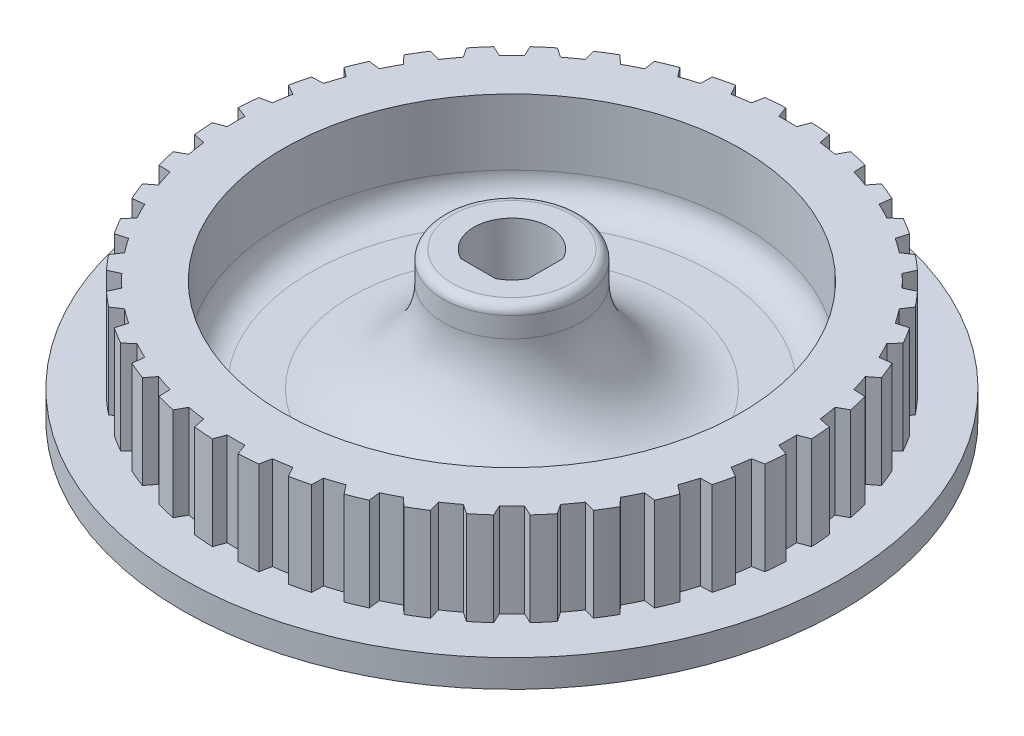
SolidWorks part; units mm, degrees
ref_plane "Спереди" through (0, 0, 0) normal (0, 0, 1) x (1, 0, 0)
ref_plane "Сверху" through (0, 0, 0) normal (0, 1, 0) x (1, 0, 0)
ref_plane "Справа" through (0, 0, 0) normal (1, 0, 0) x (0, 0, -1)
sketch "Эскиз1" plane through (0, 0, 0) normal (0, 1, 0) x (1, 0, 0)
  line L0 (0, 32.35) -> (0, 0) construction
  line L1 (0.975, 30.1342) -> (1.406, 31.3185)
  line L2 (-0.975, 30.1342) -> (-1.406, 31.3185)
  line L3 (3.751, 29.9158) -> (3.5106, 31.1528)
  line L4 (5.677, 29.6107) -> (6.288, 30.7129)
  line L5 (8.3847, 28.9606) -> (8.3407, 30.2201)
  line L6 (10.2393, 28.3581) -> (11.0151, 29.3511)
  line L7 (12.8119, 27.2924) -> (12.9655, 28.5433)
  line L8 (14.5494, 26.4072) -> (15.4711, 27.2666)
  line L9 (16.9237, 24.9522) -> (17.271, 26.1636)
  line L10 (18.5012, 23.806) -> (19.546, 24.5107)
  line L11 (20.6187, 21.9975) -> (21.1513, 23.1397)
  line L12 (21.9975, 20.6187) -> (23.1397, 21.1513)
  line L13 (23.806, 18.5012) -> (24.5107, 19.546)
  line L14 (24.9522, 16.9237) -> (26.1636, 17.271)
  line L15 (26.4072, 14.5494) -> (27.2666, 15.4711)
  line L16 (27.2924, 12.8119) -> (28.5433, 12.9655)
  line L17 (28.3581, 10.2393) -> (29.3511, 11.0151)
  line L18 (28.9606, 8.3847) -> (30.2201, 8.3407)
  line L19 (29.6107, 5.677) -> (30.7129, 6.288)
  line L20 (29.9158, 3.751) -> (31.1528, 3.5106)
  line L21 (30.1342, 0.975) -> (31.3185, 1.406)
  line L22 (30.1342, -0.975) -> (31.3185, -1.406)
  line L23 (29.9158, -3.751) -> (31.1528, -3.5106)
  line L24 (29.6107, -5.677) -> (30.7129, -6.288)
  line L25 (28.9606, -8.3847) -> (30.2201, -8.3407)
  line L26 (28.3581, -10.2393) -> (29.3511, -11.0151)
  line L27 (27.2924, -12.8119) -> (28.5433, -12.9655)
  line L28 (26.4072, -14.5494) -> (27.2666, -15.4711)
  line L29 (24.9522, -16.9237) -> (26.1636, -17.271)
  line L30 (23.806, -18.5012) -> (24.5107, -19.546)
  line L31 (21.9975, -20.6187) -> (23.1397, -21.1513)
  line L32 (20.6187, -21.9975) -> (21.1513, -23.1397)
  line L33 (18.5012, -23.806) -> (19.546, -24.5107)
  line L34 (16.9237, -24.9522) -> (17.271, -26.1636)
  line L35 (14.5494, -26.4072) -> (15.4711, -27.2666)
  line L36 (12.8119, -27.2924) -> (12.9655, -28.5433)
  line L37 (10.2393, -28.3581) -> (11.0151, -29.3511)
  line L38 (8.3847, -28.9606) -> (8.3407, -30.2201)
  line L39 (5.677, -29.6107) -> (6.288, -30.7129)
  line L40 (3.751, -29.9158) -> (3.5106, -31.1528)
  line L41 (0.975, -30.1342) -> (1.406, -31.3185)
  line L42 (-0.975, -30.1342) -> (-1.406, -31.3185)
  line L43 (-3.751, -29.9158) -> (-3.5106, -31.1528)
  line L44 (-5.677, -29.6107) -> (-6.288, -30.7129)
  line L45 (-8.3847, -28.9606) -> (-8.3407, -30.2201)
  line L46 (-10.2393, -28.3581) -> (-11.0151, -29.3511)
  line L47 (-12.8119, -27.2924) -> (-12.9655, -28.5433)
  line L48 (-14.5494, -26.4072) -> (-15.4711, -27.2666)
  line L49 (-16.9237, -24.9522) -> (-17.271, -26.1636)
  line L50 (-18.5012, -23.806) -> (-19.546, -24.5107)
  line L51 (-20.6187, -21.9975) -> (-21.1513, -23.1397)
  line L52 (-21.9975, -20.6187) -> (-23.1397, -21.1513)
  line L53 (-23.806, -18.5012) -> (-24.5107, -19.546)
  line L54 (-24.9522, -16.9237) -> (-26.1636, -17.271)
  line L55 (-26.4072, -14.5494) -> (-27.2666, -15.4711)
  line L56 (-27.2924, -12.8119) -> (-28.5433, -12.9655)
  line L57 (-28.3581, -10.2393) -> (-29.3511, -11.0151)
  line L58 (-28.9606, -8.3847) -> (-30.2201, -8.3407)
  line L59 (-29.6107, -5.677) -> (-30.7129, -6.288)
  line L60 (-29.9158, -3.751) -> (-31.1528, -3.5106)
  line L61 (-30.1342, -0.975) -> (-31.3185, -1.406)
  line L62 (-30.1342, 0.975) -> (-31.3185, 1.406)
  line L63 (-29.9158, 3.751) -> (-31.1528, 3.5106)
  line L64 (-29.6107, 5.677) -> (-30.7129, 6.288)
  line L65 (-28.9606, 8.3847) -> (-30.2201, 8.3407)
  line L66 (-28.3581, 10.2393) -> (-29.3511, 11.0151)
  line L67 (-27.2924, 12.8119) -> (-28.5433, 12.9655)
  line L68 (-26.4072, 14.5494) -> (-27.2666, 15.4711)
  line L69 (-24.9522, 16.9237) -> (-26.1636, 17.271)
  line L70 (-23.806, 18.5012) -> (-24.5107, 19.546)
  line L71 (-21.9975, 20.6187) -> (-23.1397, 21.1513)
  line L72 (-20.6187, 21.9975) -> (-21.1513, 23.1397)
  line L73 (-18.5012, 23.806) -> (-19.546, 24.5107)
  line L74 (-16.9237, 24.9522) -> (-17.271, 26.1636)
  line L75 (-14.5494, 26.4072) -> (-15.4711, 27.2666)
  line L76 (-12.8119, 27.2924) -> (-12.9655, 28.5433)
  line L77 (-10.2393, 28.3581) -> (-11.0151, 29.3511)
  line L78 (-8.3847, 28.9606) -> (-8.3407, 30.2201)
  line L79 (-5.677, 29.6107) -> (-6.288, 30.7129)
  line L80 (-3.751, 29.9158) -> (-3.5106, 31.1528)
  circle A0 centre (0, 0) radius 30.15 construction
  circle A1 centre (0, 0) radius 32.35 construction
  circle A2 centre (0, 0) radius 31.85 construction
  circle A3 centre (0, 0) radius 31.35 construction
  arc A4 (-0.975, 30.1342) -> (0.975, 30.1342) centre (0, 0) cw
  arc A5 (3.751, 29.9158) -> (5.677, 29.6107) centre (0, 0) cw
  arc A6 (8.3847, 28.9606) -> (10.2393, 28.3581) centre (0, 0) cw
  arc A7 (12.8119, 27.2924) -> (14.5494, 26.4072) centre (0, 0) cw
  arc A8 (16.9237, 24.9522) -> (18.5012, 23.806) centre (0, 0) cw
  arc A9 (20.6187, 21.9975) -> (21.9975, 20.6187) centre (0, 0) cw
  arc A10 (23.806, 18.5012) -> (24.9522, 16.9237) centre (0, 0) cw
  arc A11 (26.4072, 14.5494) -> (27.2924, 12.8119) centre (0, 0) cw
  arc A12 (28.3581, 10.2393) -> (28.9606, 8.3847) centre (0, 0) cw
  arc A13 (29.6107, 5.677) -> (29.9158, 3.751) centre (0, 0) cw
  arc A14 (30.1342, 0.975) -> (30.1342, -0.975) centre (0, 0) cw
  arc A15 (29.9158, -3.751) -> (29.6107, -5.677) centre (0, 0) cw
  arc A16 (28.9606, -8.3847) -> (28.3581, -10.2393) centre (0, 0) cw
  arc A17 (27.2924, -12.8119) -> (26.4072, -14.5494) centre (0, 0) cw
  arc A18 (24.9522, -16.9237) -> (23.806, -18.5012) centre (0, 0) cw
  arc A19 (21.9975, -20.6187) -> (20.6187, -21.9975) centre (0, 0) cw
  arc A20 (18.5012, -23.806) -> (16.9237, -24.9522) centre (0, 0) cw
  arc A21 (14.5494, -26.4072) -> (12.8119, -27.2924) centre (0, 0) cw
  arc A22 (10.2393, -28.3581) -> (8.3847, -28.9606) centre (0, 0) cw
  arc A23 (5.677, -29.6107) -> (3.751, -29.9158) centre (0, 0) cw
  arc A24 (0.975, -30.1342) -> (-0.975, -30.1342) centre (0, 0) cw
  arc A25 (-3.751, -29.9158) -> (-5.677, -29.6107) centre (0, 0) cw
  arc A26 (-8.3847, -28.9606) -> (-10.2393, -28.3581) centre (0, 0) cw
  arc A27 (-12.8119, -27.2924) -> (-14.5494, -26.4072) centre (0, 0) cw
  arc A28 (-16.9237, -24.9522) -> (-18.5012, -23.806) centre (0, 0) cw
  arc A29 (-20.6187, -21.9975) -> (-21.9975, -20.6187) centre (0, 0) cw
  arc A30 (-23.806, -18.5012) -> (-24.9522, -16.9237) centre (0, 0) cw
  arc A31 (-26.4072, -14.5494) -> (-27.2924, -12.8119) centre (0, 0) cw
  arc A32 (-28.3581, -10.2393) -> (-28.9606, -8.3847) centre (0, 0) cw
  arc A33 (-29.6107, -5.677) -> (-29.9158, -3.751) centre (0, 0) cw
  arc A34 (-30.1342, -0.975) -> (-30.1342, 0.975) centre (0, 0) cw
  arc A35 (-29.9158, 3.751) -> (-29.6107, 5.677) centre (0, 0) cw
  arc A36 (-28.9606, 8.3847) -> (-28.3581, 10.2393) centre (0, 0) cw
  arc A37 (-27.2924, 12.8119) -> (-26.4072, 14.5494) centre (0, 0) cw
  arc A38 (-24.9522, 16.9237) -> (-23.806, 18.5012) centre (0, 0) cw
  arc A39 (-21.9975, 20.6187) -> (-20.6187, 21.9975) centre (0, 0) cw
  arc A40 (-18.5012, 23.806) -> (-16.9237, 24.9522) centre (0, 0) cw
  arc A41 (-14.5494, 26.4072) -> (-12.8119, 27.2924) centre (0, 0) cw
  arc A42 (-10.2393, 28.3581) -> (-8.3847, 28.9606) centre (0, 0) cw
  arc A43 (-5.677, 29.6107) -> (-3.751, 29.9158) centre (0, 0) cw
  arc A60 (1.406, 31.3185) -> (3.5106, 31.1528) centre (0, 0) cw
  arc A61 (6.288, 30.7129) -> (8.3407, 30.2201) centre (0, 0) cw
  arc A62 (11.0151, 29.3511) -> (12.9655, 28.5433) centre (0, 0) cw
  arc A63 (15.4711, 27.2666) -> (17.271, 26.1636) centre (0, 0) cw
  arc A64 (19.546, 24.5107) -> (21.1513, 23.1397) centre (0, 0) cw
  arc A65 (23.1397, 21.1513) -> (24.5107, 19.546) centre (0, 0) cw
  arc A66 (26.1636, 17.271) -> (27.2666, 15.4711) centre (0, 0) cw
  arc A67 (28.5433, 12.9655) -> (29.3511, 11.0151) centre (0, 0) cw
  arc A68 (30.2201, 8.3407) -> (30.7129, 6.288) centre (0, 0) cw
  arc A69 (31.1528, 3.5106) -> (31.3185, 1.406) centre (0, 0) cw
  arc A70 (31.3185, -1.406) -> (31.1528, -3.5106) centre (0, 0) cw
  arc A71 (30.7129, -6.288) -> (30.2201, -8.3407) centre (0, 0) cw
  arc A72 (29.3511, -11.0151) -> (28.5433, -12.9655) centre (0, 0) cw
  arc A73 (27.2666, -15.4711) -> (26.1636, -17.271) centre (0, 0) cw
  arc A74 (24.5107, -19.546) -> (23.1397, -21.1513) centre (0, 0) cw
  arc A75 (21.1513, -23.1397) -> (19.546, -24.5107) centre (0, 0) cw
  arc A76 (17.271, -26.1636) -> (15.4711, -27.2666) centre (0, 0) cw
  arc A77 (12.9655, -28.5433) -> (11.0151, -29.3511) centre (0, 0) cw
  arc A78 (8.3407, -30.2201) -> (6.288, -30.7129) centre (0, 0) cw
  arc A79 (3.5106, -31.1528) -> (1.406, -31.3185) centre (0, 0) cw
  arc A80 (-1.406, -31.3185) -> (-3.5106, -31.1528) centre (0, 0) cw
  arc A81 (-6.288, -30.7129) -> (-8.3407, -30.2201) centre (0, 0) cw
  arc A82 (-11.0151, -29.3511) -> (-12.9655, -28.5433) centre (0, 0) cw
  arc A83 (-15.4711, -27.2666) -> (-17.271, -26.1636) centre (0, 0) cw
  arc A84 (-19.546, -24.5107) -> (-21.1513, -23.1397) centre (0, 0) cw
  arc A85 (-23.1397, -21.1513) -> (-24.5107, -19.546) centre (0, 0) cw
  arc A86 (-26.1636, -17.271) -> (-27.2666, -15.4711) centre (0, 0) cw
  arc A87 (-28.5433, -12.9655) -> (-29.3511, -11.0151) centre (0, 0) cw
  arc A88 (-30.2201, -8.3407) -> (-30.7129, -6.288) centre (0, 0) cw
  arc A89 (-31.1528, -3.5106) -> (-31.3185, -1.406) centre (0, 0) cw
  arc A90 (-31.3185, 1.406) -> (-31.1528, 3.5106) centre (0, 0) cw
  arc A91 (-30.7129, 6.288) -> (-30.2201, 8.3407) centre (0, 0) cw
  arc A92 (-29.3511, 11.0151) -> (-28.5433, 12.9655) centre (0, 0) cw
  arc A93 (-27.2666, 15.4711) -> (-26.1636, 17.271) centre (0, 0) cw
  arc A94 (-24.5107, 19.546) -> (-23.1397, 21.1513) centre (0, 0) cw
  arc A95 (-21.1513, 23.1397) -> (-19.546, 24.5107) centre (0, 0) cw
  arc A96 (-17.271, 26.1636) -> (-15.4711, 27.2666) centre (0, 0) cw
  arc A97 (-12.9655, 28.5433) -> (-11.0151, 29.3511) centre (0, 0) cw
  arc A98 (-8.3407, 30.2201) -> (-6.288, 30.7129) centre (0, 0) cw
  arc A99 (-3.5106, 31.1528) -> (-1.406, 31.3185) centre (0, 0) cw
  point P6 (0, 30.15)
  dimension "D1" = 63.7
  dimension "D2" = 64.7
  dimension "D3" = 60.3
  dimension "D4" = 62.7
  dimension "D5" = 1.95
  dimension "D6" = 20
  dimension "D7" = 20
extrude "teeth" add sketch "Эскиз1" along normal blind 10.2
sketch "Эскиз2" plane through (0, 0, 0) normal (0, 1, 0) x (1, 0, 0)
  circle A0 centre (0, 0) radius 36
  dimension "D1" = 72
extrude "base" add sketch "Эскиз2" against normal blind 3
sketch "Эскиз5" plane through (0, 10.2, 0) normal (0, 1, 0) x (1, 0, 0)
  line L0 (3.6895, 1.9) -> (3.6895, -1.9)
  line L1 (1.9, -3.6895) -> (-1.9, -3.6895)
  circle A0 centre (0, 0) radius 4.15 construction
  arc A1 (3.6895, 1.9) -> (-1.9, -3.6895) centre (0, 0) ccw
  arc A2 (1.9, -3.6895) -> (3.6895, -1.9) centre (0, 0) ccw
  dimension "D1" = 8.3
  dimension "D2" = 3.8
extrude "corner hole" cut sketch "Эскиз5" against normal blind 7
sketch "Эскиз6" plane through (0, 10.2, 0) normal (0, -1, 0) x (1, 0, 0)
  circle A0 centre (0, 0) radius 7.5
  circle A1 centre (0, 0) radius 25
  dimension "D1" = 50
  dimension "D2" = 15
extrude "save plastic hole" cut sketch "Эскиз6" along normal up to surface (10.2 mm away) up to face at (0, 0, 36)
sketch "Эскиз7" plane through (0, -3, 0) normal (0, -1, 0) x (1, 0, 0)
  circle A0 centre (0, 0) radius 4.15
  dimension "D1" = 8.3
extrude "round hole" cut sketch "Эскиз7" against normal blind 6.2
sketch "Эскиз9" plane through (0, 10.2, 0) normal (0, 1, 0) x (1, 0, 0)
  line L0 (3.6895, 1.9) -> (3.6895, -1.9)
  line L1 (1.9, -3.6895) -> (-1.9, -3.6895)
  arc A0 (1.9, -3.6895) -> (3.6895, -1.9) centre (0, 0) ccw
  arc A2 (3.6895, 1.9) -> (-1.9, -3.6895) centre (0, 0) ccw
  arc A3 (1.9, -3.6895) -> (3.6895, -1.9) centre (0, 0) ccw construction
  circle A4 centre (0, 0) radius 7.5
extrude "pin" add sketch "Эскиз9" along normal blind 3
chamfer "Фаска1" distance 0.5 angle 80 1 edges at (0, -3, -4.15)
fillet "Скругление1" radius 1 1 edges at (0, 13.2, 7.5)
fillet "Скругление2" radius 3 1 edges at (0, 0, 25)
fillet "Скругление3" radius 10 1 edges at (0, 0, 7.5)
